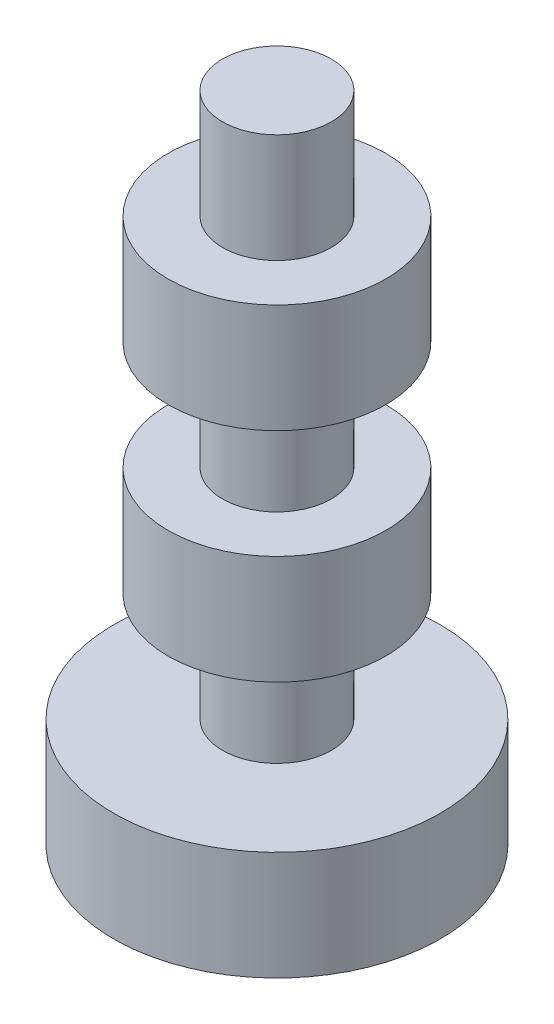
SolidWorks part; units mm, degrees
ref_plane "Front Plane" through (0, 0, 0) normal (0, 0, 1) x (1, 0, 0)
ref_plane "Top Plane" through (0, 0, 0) normal (0, 1, 0) x (1, 0, 0)
ref_plane "Right Plane" through (0, 0, 0) normal (1, 0, 0) x (0, 0, -1)
sketch "Sketch1" plane through (0, 0, 0) normal (0, 0, 1) x (1, 0, 0)
  line L0 (0, 0) -> (0, 38.1) construction
  line L1 (0, 0) -> (9.525, 0)
  line L2 (9.525, 0) -> (9.525, 6.35)
  line L3 (9.525, 6.35) -> (3.175, 6.35)
  line L4 (3.175, 6.35) -> (3.175, 12.7)
  line L5 (3.175, 12.7) -> (6.35, 12.7)
  line L6 (6.35, 12.7) -> (6.35, 19.05)
  line L7 (6.35, 19.05) -> (3.175, 19.05)
  line L8 (3.175, 19.05) -> (3.175, 25.4)
  line L9 (3.175, 25.4) -> (6.35, 25.4)
  line L10 (6.35, 25.4) -> (6.35, 31.75)
  line L11 (6.35, 31.75) -> (3.175, 31.75)
  line L12 (3.175, 31.75) -> (3.175, 38.1)
  line L13 (3.175, 38.1) -> (0, 38.1)
  line L14 (0, 0) -> (0, 38.1)
  dimension "D1" = 6.35
  dimension "D2" = 6.35
  dimension "D3" = 19.05
  dimension "D4" = 12.7
  dimension "D5" = 6.35
revolve "Revolve1" add sketch "Sketch1" angle 360 about L0
